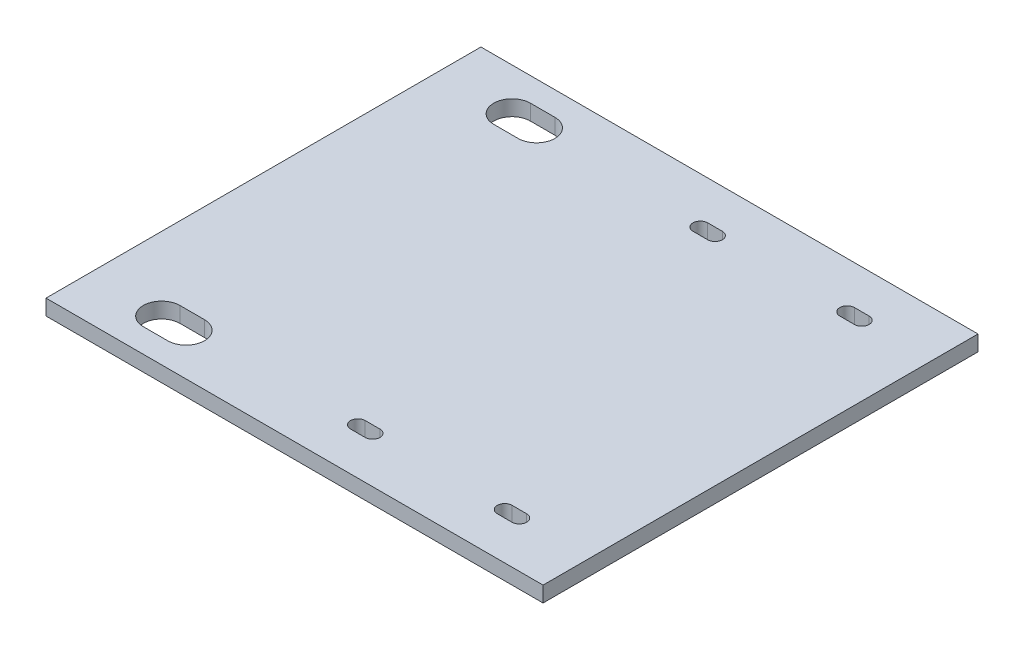
SolidWorks part; units mm, degrees
material "1023 Carbon Steel Sheet (SS)"
ref_plane "Front Plane" through (0, 0, 0) normal (0, 0, 1) x (1, 0, 0)
ref_plane "Top Plane" through (0, 0, 0) normal (0, 1, 0) x (1, 0, 0)
ref_plane "Right Plane" through (0, 0, 0) normal (1, 0, 0) x (0, 0, -1)
sketch "Sketch1" plane through (0, 0, 0) normal (0, 1, 0) x (1, 0, 0)
  line L1 (50.8, -44.45) -> (-50.8, -44.45)
  line L2 (50.8, -44.45) -> (50.8, 44.45)
  line L3 (50.8, 44.45) -> (-50.8, 44.45)
  line L4 (-50.8, -44.45) -> (-50.8, 44.45)
  line L5 (50.8, -44.45) -> (-50.8, 44.45) construction
  line L6 (50.8, 44.45) -> (-50.8, -44.45) construction
  point P0 (0, 0)
  dimension "D1" = 88.9
  dimension "D2" = 101.6
extrude "Boss-Extrude1" add sketch "Sketch1" along normal blind 3.175
sketch "Sketch2" plane through (0, 3.175, 0) normal (0, 1, 0) x (1, 0, 0)
  line L0 (-35.8, 35.814) -> (-30.8, 35.814) construction
  line L1 (-35.8, 39.564) -> (-30.8, 39.564)
  line L2 (-35.8, 32.064) -> (-30.8, 32.064)
  line L3 (-33.3, 35.814) -> (-33.3, -35.814) construction
  line L4 (-35.8, -35.814) -> (-30.8, -35.814) construction
  line L5 (-35.8, -32.064) -> (-30.8, -32.064)
  line L6 (-35.8, -39.564) -> (-30.8, -39.564)
  line L7 (3.5, 35) -> (6.5, 35) construction
  line L10 (35, -35) -> (5, -35) construction
  line L11 (35, -35) -> (35, 35) construction
  line L14 (35, 35) -> (5, 35) construction
  line L15 (-50.8, 44.45) -> (-50.8, -44.45) construction
  line L16 (5, -35) -> (5, 35) construction
  line L17 (35, -35) -> (5, 35) construction
  line L18 (35, 35) -> (5, -35) construction
  line L19 (3.5, 36.5) -> (6.5, 36.5)
  line L20 (3.5, 33.5) -> (6.5, 33.5)
  line L21 (33.5, 35) -> (36.5, 35) construction
  line L22 (33.5, 36.5) -> (36.5, 36.5)
  line L23 (33.5, 33.5) -> (36.5, 33.5)
  line L24 (3.5, -35) -> (6.5, -35) construction
  line L25 (3.5, -33.5) -> (6.5, -33.5)
  line L26 (3.5, -36.5) -> (6.5, -36.5)
  line L27 (33.5, -35) -> (36.5, -35) construction
  line L28 (33.5, -33.5) -> (36.5, -33.5)
  line L29 (33.5, -36.5) -> (36.5, -36.5)
  arc A0 (-35.8, 39.564) -> (-35.8, 32.064) centre (-35.8, 35.814) ccw
  arc A1 (-30.8, 32.064) -> (-30.8, 39.564) centre (-30.8, 35.814) ccw
  arc A2 (-35.8, -32.064) -> (-35.8, -39.564) centre (-35.8, -35.814) ccw
  arc A3 (-30.8, -39.564) -> (-30.8, -32.064) centre (-30.8, -35.814) ccw
  arc A4 (3.5, 36.5) -> (3.5, 33.5) centre (3.5, 35) ccw
  arc A5 (6.5, 33.5) -> (6.5, 36.5) centre (6.5, 35) ccw
  arc A6 (33.5, 36.5) -> (33.5, 33.5) centre (33.5, 35) ccw
  arc A7 (36.5, 33.5) -> (36.5, 36.5) centre (36.5, 35) ccw
  arc A8 (3.5, -33.5) -> (3.5, -36.5) centre (3.5, -35) ccw
  arc A9 (6.5, -36.5) -> (6.5, -33.5) centre (6.5, -35) ccw
  arc A10 (33.5, -33.5) -> (33.5, -36.5) centre (33.5, -35) ccw
  arc A11 (36.5, -36.5) -> (36.5, -33.5) centre (36.5, -35) ccw
  point P2 (-33.3, 35.814)
  point P11 (-33.3, -35.814)
  point P16 (20, 0)
  point P17 (-33.3, 0)
  point P23 (5, 35)
  point P30 (15, 35)
  point P31 (35, 35)
  point P40 (5, -35)
  point P47 (35, -35)
  point P54 (31.571, 24.2621)
  point P55 (45, 35)
  point P56 (21.1953, -3.3855)
  point P57 (15, -35)
  point P58 (45, -35)
  dimension "D1" = 7.5
  dimension "D2" = 5
  dimension "D3" = 71.628
  dimension "D4" = 17.5
  dimension "D5" = 30
  dimension "D6" = 70
  dimension "D7" = 20
  dimension "D8" = 3
  dimension "D9" = 3
extrude "Cut-Extrude1" cut sketch "Sketch2" against normal through all
